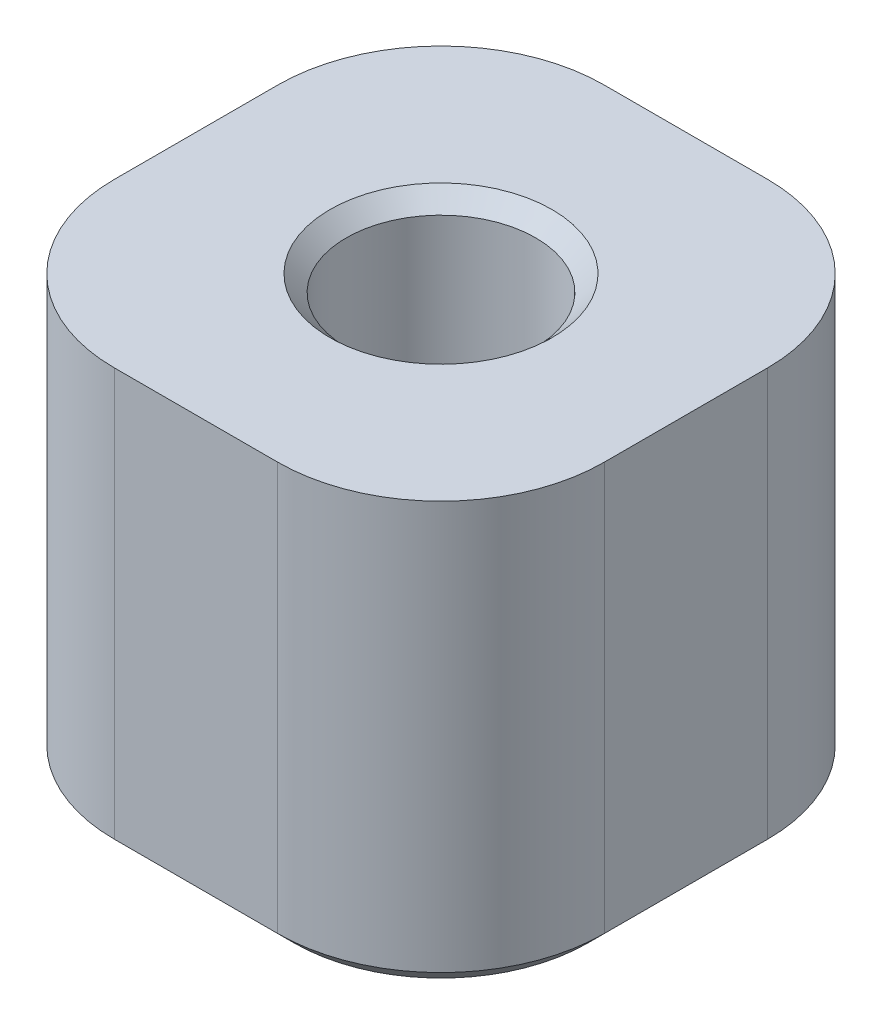
SolidWorks part; units mm, degrees
ref_plane "Спереди" through (0, 0, 0) normal (0, 0, 1) x (1, 0, 0)
ref_plane "Сверху" through (0, 0, 0) normal (0, 1, 0) x (1, 0, 0)
ref_plane "Справа" through (0, 0, 0) normal (1, 0, 0) x (0, 0, -1)
sketch "Эскиз1" plane through (0, 0, 0) normal (0, 1, 0) x (1, 0, 0)
  line L1 (-15, -15) -> (15, -15)
  line L2 (-15, -15) -> (-15, 15)
  line L3 (-15, 15) -> (15, 15)
  line L4 (15, -15) -> (15, 15)
  line L5 (0, 15) -> (0, -15) construction
  line L6 (-15, 0) -> (15, 0) construction
  point P0 (0, 0)
  dimension "D1" = 30
extrude "Бобышка-Вытянуть1" add sketch "Эскиз1" along normal blind 26
sketch "Эскиз2" plane through (0, 26, 0) normal (0, 1, 0) x (1, 0, 0)
  circle A0 centre (0, 0) radius 5.8
  dimension "D1" = 11.6
extrude "Вырез-Вытянуть1" cut sketch "Эскиз2" against normal blind 20
fillet "Скругление1" radius 10 4 edges at (-15, 13, -15) (15, 13, -15) (-15, 13, 15) (15, 13, 15)
chamfer "Фаска1" distance 1 angle 45 8 edges at (-12.0711, 0, 12.0711) (0, 0, 15) (12.0711, 0, 12.0711) (15, 0, 0) (12.0711, 0, -12.0711) (0, 0, -15) (-12.0711, 0, -12.0711) (-15, 0, 0)
chamfer "Фаска2" distance 1 angle 45 1 edges at (0, 26, 5.8)
